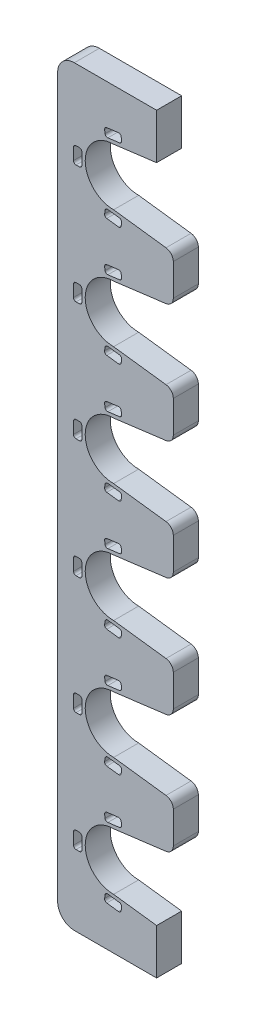
SolidWorks part; units mm, degrees
ref_plane "Front" through (0, 0, 0) normal (0, 0, 1) x (1, 0, 0)
ref_plane "Top" through (0, 0, 0) normal (0, 1, 0) x (1, 0, 0)
ref_plane "Right" through (0, 0, 0) normal (1, 0, 0) x (0, 0, -1)
sketch "Esquisse1" plane through (0, 0, 0) normal (0, 0, 1) x (1, 0, 0)
  line L1 (0, 0) -> (47, 0)
  line L2 (0, 0) -> (0, 450)
  line L3 (0, 450) -> (47, 450)
  line L4 (47, 0) -> (47, 450)
  dimension "D1" = 47
  dimension "D2" = 450
extrude "Boss.-Extru.1" add sketch "Esquisse1" along normal blind 15
sketch "Esquisse2" plane through (0, 0, 15) normal (0, 0, 1) x (1, 0, 0)
  line L0 (23.5, 0) -> (23.5, 450) construction
  line L1 (0, 0) -> (47, 0) construction
  line L2 (47, 450) -> (0, 450) construction
  line L3 (23.5, 225) -> (0, 225) construction
  line L4 (23.5, 154) -> (0, 154) construction
  line L5 (0, 450) -> (0, 0) construction
  line L6 (23.5, 83) -> (0, 83) construction
  line L7 (23.5, 367) -> (0, 367) construction
  line L8 (23.5, 296) -> (0, 296) construction
  circle A0 centre (23.5, 260.5) radius 17
  circle A1 centre (23.5, 189.5) radius 17
  circle A2 centre (23.5, 118.5) radius 17
  circle A3 centre (23.5, 47.5) radius 17
  circle A4 centre (23.5, 402.5) radius 17
  circle A5 centre (23.5, 331.5) radius 17
  dimension "D1" = 71
  dimension "D2" = 34
  dimension "D3" = 71
  dimension "D4" = 71
extrude "Enlèv. mat.-Extru.1" cut sketch "Esquisse2" against normal through all both and the other way through all
sketch "Esquisse3" plane through (0, 0, 15) normal (0, 0, 1) x (1, 0, 0)
  line L0 (23.5, 189.5) -> (23.5, 260.5) construction
  line L1 (23.5, 225) -> (0, 225) construction
  line L2 (0, 450) -> (0, 0) construction
  line L3 (23.5, 243.5) -> (47, 240.5)
  line L4 (47, 0) -> (47, 450) construction
  line L5 (47, 240.5) -> (47, 280.5)
  line L6 (47, 260.5) -> (23.5, 260.5) construction
  line L7 (23.5, 277.5) -> (47, 280.5)
  line L8 (23.5, 243.5) -> (23.5, 277.5)
  line L9 (47, 189.5) -> (23.5, 189.5) construction
  line L10 (23.5, 172.5) -> (47, 169.5)
  line L11 (47, 209.5) -> (47, 169.5)
  line L12 (23.5, 206.5) -> (47, 209.5)
  line L13 (23.5, 206.5) -> (23.5, 172.5)
  line L14 (23.5, 172.5) -> (23.5, 135.5) construction
  line L15 (23.5, 64.5) -> (23.5, 101.5) construction
  line L16 (23.5, 83) -> (0, 83) construction
  line L17 (23.5, 154) -> (0, 154) construction
  line L18 (47, 118.5) -> (23.5, 118.5) construction
  line L19 (23.5, 101.5) -> (23.5, 135.5)
  line L20 (23.5, 101.5) -> (47, 98.5)
  line L21 (47, 98.5) -> (47, 138.5)
  line L22 (23.5, 135.5) -> (47, 138.5)
  line L23 (47, 47.5) -> (23.5, 47.5) construction
  line L24 (23.5, 30.5) -> (47, 27.5)
  line L25 (47, 67.5) -> (47, 27.5)
  line L26 (23.5, 64.5) -> (47, 67.5)
  line L27 (23.5, 64.5) -> (23.5, 30.5)
  line L28 (47, 402.5) -> (23.5, 402.5) construction
  line L29 (47, 331.5) -> (23.5, 331.5) construction
  line L30 (23.5, 296) -> (0, 296) construction
  line L31 (23.5, 367) -> (0, 367) construction
  line L32 (23.5, 385.5) -> (23.5, 348.5) construction
  line L33 (23.5, 385.5) -> (23.5, 419.5)
  line L34 (23.5, 385.5) -> (47, 382.5)
  line L35 (47, 382.5) -> (47, 422.5)
  line L36 (23.5, 419.5) -> (47, 422.5)
  line L37 (23.5, 314.5) -> (47, 311.5)
  line L38 (47, 351.5) -> (47, 311.5)
  line L39 (23.5, 348.5) -> (47, 351.5)
  line L40 (23.5, 348.5) -> (23.5, 314.5)
  circle A0 centre (23.5, 260.5) radius 17 construction
  circle A1 centre (23.5, 118.5) radius 17 construction
  circle A2 centre (23.5, 47.5) radius 17 construction
  dimension "D1" = 3
extrude "Enlèv. mat.-Extru.2" cut sketch "Esquisse3" against normal through all both and the other way through all
sketch "Esquisse4" plane through (0, 0, 15) normal (0, 0, 1) x (1, 0, 0)
  line L0 (47, 450) -> (0, 450) construction
  line L1 (0, 0) -> (-10, 0)
  line L2 (0, 0) -> (0, 450)
  line L3 (0, 450) -> (-10, 450)
  line L4 (-10, 0) -> (-10, 450)
  dimension "D1" = 10
extrude "Boss.-Extru.2" add sketch "Esquisse4" against normal up to vertex (15 mm away)
sketch "Esquisse5" plane through (0, 0, 15) normal (0, 0, 1) x (1, 0, 0)
  line L0 (47, 367) -> (-10, 367) construction
  line L1 (47, 351.5) -> (47, 382.5) construction
  line L2 (-10, 450) -> (-10, 0) construction
  line L3 (47, 296) -> (-10, 296) construction
  line L4 (47, 280.5) -> (47, 311.5) construction
  line L5 (47, 225) -> (-10, 225) construction
  line L6 (47, 209.5) -> (47, 240.5) construction
  line L7 (47, 154) -> (-10, 154) construction
  line L8 (47, 138.5) -> (47, 169.5) construction
  line L9 (47, 83) -> (-10, 83) construction
  line L10 (47, 67.5) -> (47, 98.5) construction
  line L11 (4.5, 189.5) -> (6.5, 189.5) construction
  line L12 (-0.5, 194.5) -> (4.5, 194.5)
  line L13 (-0.5, 194.5) -> (-0.5, 184.5)
  line L14 (-0.5, 184.5) -> (4.5, 184.5)
  line L15 (4.5, 194.5) -> (4.5, 184.5)
  line L16 (47, 169.5) -> (47, 209.5) construction
  line L17 (47, 189.5) -> (6.5, 189.5) construction
  line L18 (18.564, 207.8861) -> (28.4835, 209.1524)
  line L19 (23.5, 206.5) -> (47, 209.5) construction
  line L20 (18.564, 207.8861) -> (17.9308, 212.8458)
  line L21 (17.9308, 212.8458) -> (27.8503, 214.1122)
  line L22 (27.8503, 214.1122) -> (28.4835, 209.1524)
  line L23 (18.564, 207.8861) -> (26.75, 189.5) construction
  line L24 (27.8503, 164.8878) -> (28.4835, 169.8476)
  line L25 (17.9308, 166.1542) -> (27.8503, 164.8878)
  line L26 (18.564, 171.1139) -> (17.9308, 166.1542)
  line L27 (18.564, 171.1139) -> (28.4835, 169.8476)
  line L28 (18.564, 100.1139) -> (26.75, 118.5) construction
  line L29 (47, 118.5) -> (6.5, 118.5) construction
  line L30 (47, 138.5) -> (47, 98.5) construction
  line L31 (4.5, 118.5) -> (6.5, 118.5) construction
  line L32 (18.564, 136.8861) -> (28.4835, 138.1524)
  line L33 (18.564, 136.8861) -> (17.9308, 141.8458)
  line L34 (17.9308, 141.8458) -> (27.8503, 143.1122)
  line L35 (27.8503, 143.1122) -> (28.4835, 138.1524)
  line L36 (27.8503, 93.8878) -> (28.4835, 98.8476)
  line L37 (17.9308, 95.1542) -> (27.8503, 93.8878)
  line L38 (18.564, 100.1139) -> (17.9308, 95.1542)
  line L39 (18.564, 100.1139) -> (28.4835, 98.8476)
  line L40 (4.5, 113.5) -> (4.5, 123.5)
  line L41 (-0.5, 123.5) -> (4.5, 123.5)
  line L42 (-0.5, 113.5) -> (-0.5, 123.5)
  line L43 (-0.5, 113.5) -> (4.5, 113.5)
  line L44 (4.5, 47.5) -> (6.5, 47.5) construction
  line L45 (47, 27.5) -> (47, 67.5) construction
  line L46 (47, 47.5) -> (6.5, 47.5) construction
  line L47 (18.564, 65.8861) -> (26.75, 47.5) construction
  line L48 (-0.5, 52.5) -> (4.5, 52.5)
  line L49 (-0.5, 52.5) -> (-0.5, 42.5)
  line L50 (-0.5, 42.5) -> (4.5, 42.5)
  line L51 (4.5, 52.5) -> (4.5, 42.5)
  line L52 (18.564, 65.8861) -> (28.4835, 67.1524)
  line L53 (18.564, 65.8861) -> (17.9308, 70.8458)
  line L54 (17.9308, 70.8458) -> (27.8503, 72.1122)
  line L55 (27.8503, 72.1122) -> (28.4835, 67.1524)
  line L56 (27.8503, 22.8878) -> (28.4835, 27.8476)
  line L57 (17.9308, 24.1542) -> (27.8503, 22.8878)
  line L58 (18.564, 29.1139) -> (17.9308, 24.1542)
  line L59 (18.564, 29.1139) -> (28.4835, 27.8476)
  line L60 (18.564, 384.1139) -> (26.75, 402.5) construction
  line L61 (47, 402.5) -> (6.5, 402.5) construction
  line L62 (47, 422.5) -> (47, 382.5) construction
  line L63 (4.5, 402.5) -> (6.5, 402.5) construction
  line L64 (4.5, 331.5) -> (6.5, 331.5) construction
  line L65 (47, 311.5) -> (47, 351.5) construction
  line L66 (47, 331.5) -> (6.5, 331.5) construction
  line L67 (18.564, 349.8861) -> (26.75, 331.5) construction
  line L68 (18.564, 242.1139) -> (26.75, 260.5) construction
  line L69 (47, 260.5) -> (6.5, 260.5) construction
  line L70 (47, 280.5) -> (47, 240.5) construction
  line L71 (4.5, 260.5) -> (6.5, 260.5) construction
  line L72 (47, 367) -> (-10, 367) construction
  line L73 (47, 296) -> (-10, 296) construction
  line L74 (18.564, 420.8861) -> (28.4835, 422.1524)
  line L75 (18.564, 420.8861) -> (17.9308, 425.8458)
  line L76 (17.9308, 425.8458) -> (27.8503, 427.1122)
  line L77 (27.8503, 427.1122) -> (28.4835, 422.1524)
  line L78 (27.8503, 377.8878) -> (28.4835, 382.8476)
  line L79 (17.9308, 379.1542) -> (27.8503, 377.8878)
  line L80 (18.564, 384.1139) -> (17.9308, 379.1542)
  line L81 (18.564, 384.1139) -> (28.4835, 382.8476)
  line L82 (4.5, 397.5) -> (4.5, 407.5)
  line L83 (-0.5, 407.5) -> (4.5, 407.5)
  line L84 (-0.5, 397.5) -> (-0.5, 407.5)
  line L85 (-0.5, 397.5) -> (4.5, 397.5)
  line L86 (-0.5, 336.5) -> (4.5, 336.5)
  line L87 (-0.5, 336.5) -> (-0.5, 326.5)
  line L88 (-0.5, 326.5) -> (4.5, 326.5)
  line L89 (4.5, 336.5) -> (4.5, 326.5)
  line L90 (18.564, 349.8861) -> (28.4835, 351.1524)
  line L91 (18.564, 349.8861) -> (17.9308, 354.8458)
  line L92 (17.9308, 354.8458) -> (27.8503, 356.1122)
  line L93 (27.8503, 356.1122) -> (28.4835, 351.1524)
  line L94 (27.8503, 306.8878) -> (28.4835, 311.8476)
  line L95 (17.9308, 308.1542) -> (27.8503, 306.8878)
  line L96 (18.564, 313.1139) -> (17.9308, 308.1542)
  line L97 (18.564, 313.1139) -> (28.4835, 311.8476)
  line L98 (18.564, 278.8861) -> (28.4835, 280.1524)
  line L99 (18.564, 278.8861) -> (17.9308, 283.8458)
  line L100 (17.9308, 283.8458) -> (27.8503, 285.1122)
  line L101 (27.8503, 285.1122) -> (28.4835, 280.1524)
  line L102 (27.8503, 235.8878) -> (28.4835, 240.8476)
  line L103 (17.9308, 237.1542) -> (27.8503, 235.8878)
  line L104 (18.564, 242.1139) -> (17.9308, 237.1542)
  line L105 (18.564, 242.1139) -> (28.4835, 240.8476)
  line L106 (4.5, 255.5) -> (4.5, 265.5)
  line L107 (-0.5, 265.5) -> (4.5, 265.5)
  line L108 (-0.5, 255.5) -> (-0.5, 265.5)
  line L109 (-0.5, 255.5) -> (4.5, 255.5)
  arc A1 (23.5, 206.5) -> (23.5, 172.5) centre (23.5, 189.5) ccw construction
  dimension "D1" = 5
  dimension "D2" = 10
  dimension "D3" = 2
  dimension "D4" = 10
  dimension "D5" = 5
  dimension "D6" = 2
  dimension "D7" = 66
extrude "Enlèv. mat.-Extru.3" cut sketch "Esquisse5" against normal blind 10
fillet "Congé2" radius 10 2 edges at (-10, 450, 7.5) (-10, 0, 7.5)
fillet "Congé3" radius 1.5 72 edges at (17.9308, 425.8458, 10) (18.564, 420.8861, 10) (28.4835, 422.1524, 10) (27.8503, 427.1122, 10) (28.4835, 311.8476, 10) (27.8503, 306.8878, 10) (17.9308, 308.1542, 10) (18.564, 313.1139, 10) (-0.5, 336.5, 10) (4.5, 336.5, 10) (-0.5, 326.5, 10) (4.5, 326.5, 10) (28.4835, 351.1524, 10) (18.564, 349.8861, 10) (17.9308, 354.8458, 10) (27.8503, 356.1122, 10) (28.4835, 382.8476, 10) (27.8503, 377.8878, 10) (17.9308, 379.1542, 10) (18.564, 384.1139, 10) (4.5, 397.5, 10) (-0.5, 397.5, 10) (-0.5, 407.5, 10) (4.5, 407.5, 10) (27.8503, 22.8878, 10) (17.9308, 24.1542, 10) (18.564, 29.1139, 10) (28.4835, 27.8476, 10) (4.5, 42.5, 10) (-0.5, 42.5, 10) (-0.5, 52.5, 10) (4.5, 52.5, 10) (18.564, 65.8861, 10) (17.9308, 70.8458, 10) (27.8503, 72.1122, 10) (28.4835, 67.1524, 10) (27.8503, 93.8878, 10) (17.9308, 95.1542, 10) (28.4835, 98.8476, 10) (18.564, 100.1139, 10) (4.5, 113.5, 10) (-0.5, 113.5, 10) (-0.5, 123.5, 10) (4.5, 123.5, 10) (28.4835, 138.1524, 10) (27.8503, 143.1122, 10) (17.9308, 141.8458, 10) (18.564, 136.8861, 10) (17.9308, 166.1542, 10) (27.8503, 164.8878, 10) (28.4835, 169.8476, 10) (18.564, 171.1139, 10) (-0.5, 184.5, 10) (4.5, 184.5, 10) (4.5, 194.5, 10) (-0.5, 194.5, 10) (17.9308, 212.8458, 10) (18.564, 207.8861, 10) (28.4835, 209.1524, 10) (27.8503, 214.1122, 10) (28.4835, 240.8476, 10) (27.8503, 235.8878, 10) (17.9308, 237.1542, 10) (18.564, 242.1139, 10) (4.5, 255.5, 10) (4.5, 265.5, 10) (-0.5, 265.5, 10) (-0.5, 255.5, 10) (27.8503, 285.1122, 10) (28.4835, 280.1524, 10) (18.564, 278.8861, 10) (17.9308, 283.8458, 10)
sketch "Esquisse6" plane through (0, 0, 15) normal (0, 0, 1) x (1, 0, 0)
  line L0 (47, 209.5) -> (59.25, 211.0638)
  line L1 (59.25, 211.0638) -> (59.25, 238.9362)
  line L2 (59.25, 225) -> (47, 225) construction
  line L3 (47, 209.5) -> (47, 240.5) construction
  line L4 (23.5, 206.5) -> (47, 209.5) construction
  line L5 (47, 240.5) -> (59.25, 238.9362)
  line L6 (6.5, 189.5) -> (80.01, 189.5) construction
  line L7 (59.25, 154) -> (47, 154) construction
  line L8 (47, 138.5) -> (59.25, 140.0638)
  line L9 (59.25, 167.9362) -> (59.25, 140.0638)
  line L10 (47, 169.5) -> (59.25, 167.9362)
  line L11 (6.5, 118.5) -> (80.01, 118.5) construction
  line L12 (59.25, 83) -> (47, 83) construction
  line L13 (47, 67.5) -> (59.25, 69.0638)
  line L14 (59.25, 69.0638) -> (59.25, 96.9362)
  line L15 (47, 98.5) -> (59.25, 96.9362)
  line L16 (6.5, 47.5) -> (85.458, 47.5) construction
  line L17 (47, 422.5) -> (49.25, 422.7872)
  line L18 (49.25, 422.7872) -> (49.25, 450)
  line L19 (49.25, 450) -> (47, 450)
  line L20 (23.5, 419.5) -> (47, 422.5) construction
  line L21 (6.5, 260.5) -> (85.458, 260.5) construction
  line L22 (6.5, 331.5) -> (117.0943, 331.5) construction
  line L23 (6.5, 402.5) -> (106.582, 402.5) construction
  line L24 (59.25, 296) -> (47, 296) construction
  line L25 (47, 280.5) -> (59.25, 282.0638)
  line L26 (59.25, 309.9362) -> (59.25, 282.0638)
  line L27 (47, 311.5) -> (59.25, 309.9362)
  line L28 (59.25, 367) -> (47, 367) construction
  line L29 (47, 351.5) -> (59.25, 353.0638)
  line L30 (59.25, 353.0638) -> (59.25, 380.9362)
  line L31 (47, 382.5) -> (59.25, 380.9362)
  line L32 (47, 422.5) -> (47, 450)
  line L33 (49.25, 0) -> (47, 0)
  line L34 (49.25, 27.2128) -> (49.25, 0)
  line L35 (47, 27.5) -> (49.25, 27.2128)
  line L36 (47, 351.5) -> (47, 382.5)
  line L37 (47, 280.5) -> (47, 311.5)
  line L38 (47, 209.5) -> (47, 240.5)
  line L39 (47, 138.5) -> (47, 169.5)
  line L40 (47, 67.5) -> (47, 98.5)
  line L41 (47, 27.5) -> (47, 0)
  arc A0 (23.5, 206.5) -> (23.5, 172.5) centre (23.5, 189.5) ccw construction
  arc A1 (23.5, 135.5) -> (23.5, 101.5) centre (23.5, 118.5) ccw construction
  arc A2 (23.5, 64.5) -> (23.5, 30.5) centre (23.5, 47.5) ccw construction
  arc A4 (23.5, 277.5) -> (23.5, 243.5) centre (23.5, 260.5) ccw construction
  arc A5 (23.5, 348.5) -> (23.5, 314.5) centre (23.5, 331.5) ccw construction
  arc A6 (23.5, 419.5) -> (23.5, 385.5) centre (23.5, 402.5) ccw construction
  dimension "D1" = 12.25
  dimension "D2" = 2.25
extrude "Boss.-Extru.3" add sketch "Esquisse6" against normal up to vertex (15 mm away)
fillet "Congé4" radius 5 10 edges at (59.25, 380.9362, 7.5) (59.25, 353.0638, 7.5) (59.25, 309.9362, 7.5) (59.25, 282.0638, 7.5) (59.25, 238.9362, 7.5) (59.25, 211.0638, 7.5) (59.25, 167.9362, 7.5) (59.25, 140.0638, 7.5) (59.25, 96.9362, 7.5) (59.25, 69.0638, 7.5)
